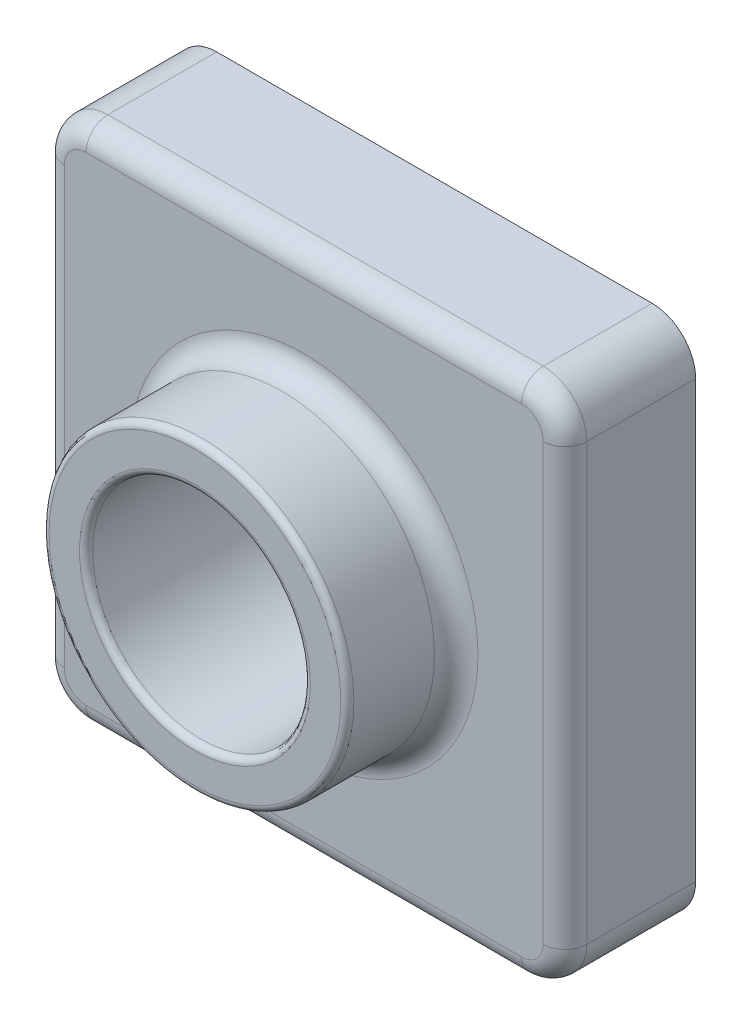
SolidWorks part; units mm, degrees
material "Chrome Stainless Steel"
ref_plane "Front Plane" through (0, 0, 0) normal (0, 0, 1) x (1, 0, 0)
ref_plane "Top Plane" through (0, 0, 0) normal (0, 1, 0) x (1, 0, 0)
ref_plane "Right Plane" through (0, 0, 0) normal (1, 0, 0) x (0, 0, -1)
sketch "Sketch3" plane through (0, 0, 0) normal (0, 0, 1) x (1, 0, 0)
  line L1 (-60, -60) -> (60, -60)
  line L2 (-60, -60) -> (-60, 60)
  line L3 (-60, 60) -> (60, 60)
  line L4 (60, -60) -> (60, 60)
  line L5 (-60, -60) -> (60, 60) construction
  line L6 (-60, 60) -> (60, -60) construction
  point P0 (0, 0)
  dimension "D1" = 120
  dimension "D2" = 120
extrude "Boss-Extrude1" add sketch "Sketch3" along normal blind 30 contours L3 L4 L1 L2
sketch "Sketch4" plane through (0, 0, 30) normal (0, 0, 1) x (1, 0, 0)
  circle A0 centre (0, 0) radius 35
  dimension "D1" = 70
extrude "Boss-Extrude2" add sketch "Sketch4" along normal blind 25
sketch "Sketch5" plane through (0, 0, 55) normal (0, 0, 1) x (1, 0, 0)
  circle A4 centre (0, 0) radius 25
  circle A5 centre (0, 0) radius 25
  dimension "D1" = 10
extrude "Cut-Extrude1" cut sketch "Sketch5" against normal through all
fillet "Fillet2" radius 1.5 2 edges at (35, 0, 55) (25, 0, 55)
fillet "Fillet3" radius 10 4 edges at (-60, 60, 15) (-60, -60, 15) (60, -60, 15) (60, 60, 15)
shell "Shell1" thickness 2
fillet "Fillet4" radius 5 9 edges at (57.0711, 57.0711, 30) (60, 0, 30) (57.0711, -57.0711, 30) (0, -60, 30) (-57.0711, -57.0711, 30) (-60, 0, 30) (-57.0711, 57.0711, 30) (0, 60, 30) (35, 0, 30)
